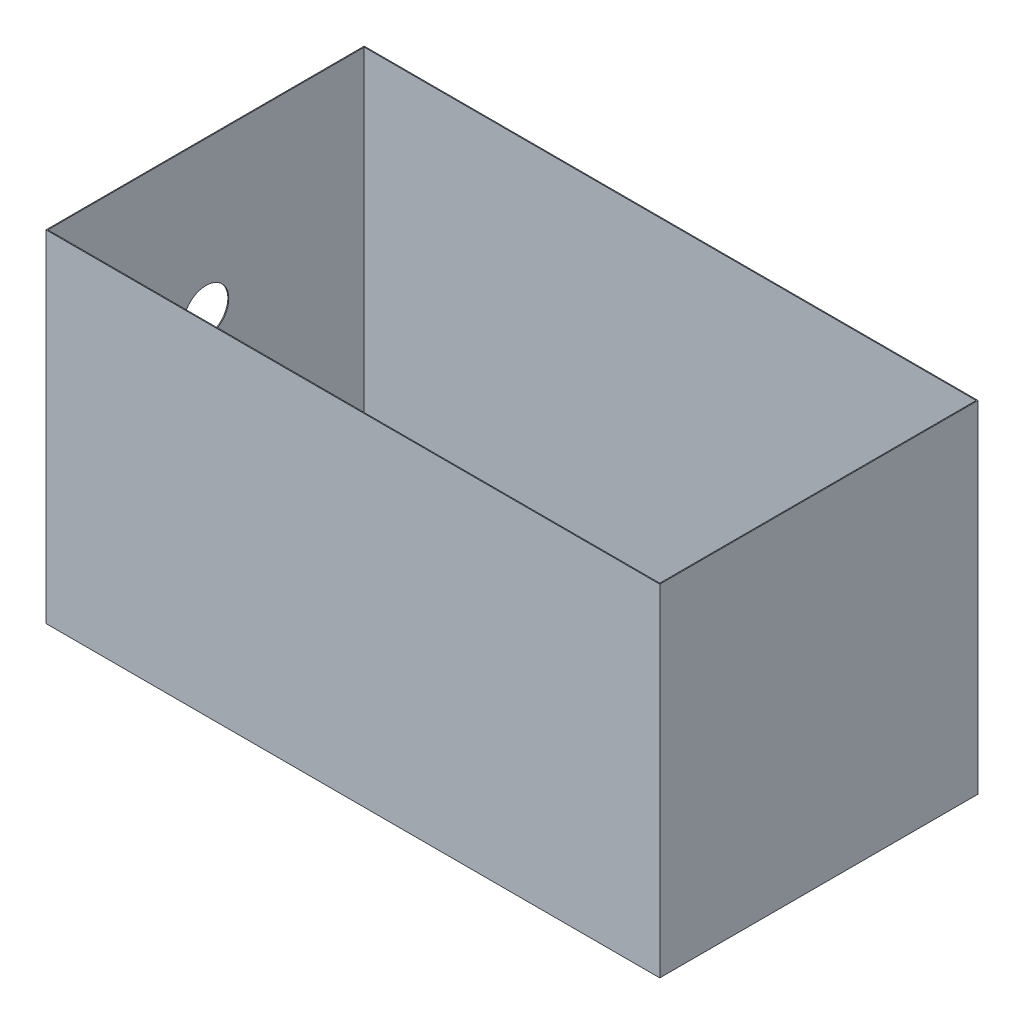
SolidWorks part; units mm, degrees
ref_plane "Спереди" through (0, 0, 0) normal (0, 0, 1) x (1, 0, 0)
ref_plane "Сверху" through (0, 0, 0) normal (0, 1, 0) x (1, 0, 0)
ref_plane "Справа" through (0, 0, 0) normal (1, 0, 0) x (0, 0, -1)
sketch "MASTER_FOOTPRINT" plane through (0, 0, 0) normal (0, 1, 0) x (1, 0, 0)
  line L1 (0, 0) -> (1350, 0)
  line L2 (0, 0) -> (0, 700)
  line L3 (0, 700) -> (1350, 700)
  line L4 (1350, 0) -> (1350, 700)
  dimension "D1" = 1350
  dimension "D2" = 700
extrude "BATH_BASE_PLATE" add sketch "MASTER_FOOTPRINT" along normal blind 750
shell "BATH_SHELL_2MM" thickness 2
sketch "Эскиз1" plane through (0, 0, 0) normal (1, 0, 0) x (0, 0, -1)
  circle A0 centre (350, 420) radius 50
extrude "INLET_D100_CUT" cut sketch "Эскиз1" along normal blind 10
equation "\"AI_Q_Peak\"= 0.006"
equation "\"AI_B_Bath\"= 700"
equation "\"AI_L_Settle\"= 900"
equation "\"AI_L_Inlet\"= 250"
equation "\"AI_L_Outlet\"= 200"
equation "\"AI_L_Bath\"= 1350"
equation "\"AI_H_Water\"= 550"
equation "\"AI_H_Freeboard\"= 200"
equation "\"AI_H_Bath\"= 750"
equation "\"AI_Shell_Thickness\"= 2"
equation "\"AI_Inlet_DN\"= 100"
equation "\"AI_Weir_Width\"= 600"
equation "\"AI_Inlet_Baffle_Offset\"= 125"
equation "\"AI_Distributor_Open_Area\"= 0.28"
equation "\"AI_Distributor_Hole_Dia\"= 22"
equation "\"AI_Distributor_Blind_Zone\"= 110"
equation "\"AI_Outlet_Baffle_Depth\"= 250"
equation "\"AI_Screw_Diameter\"= 100"
equation "\"AI_Screw_Pitch\"= 100"
equation "\"AI_Screw_Angle\"= 30"
equation "\"AI_Screw_Rpm\"= 15"
equation "\"AI_Screw_Clearance\"= 5"
equation "\"AI_Liner_Thickness\"= 5"
equation "\"AI_Discharge_Height\"= 650"
equation "\"AI_Frame_Height\"= 500"
equation "\"D1@MASTER_FOOTPRINT\" = \"AI_L_Bath\""
equation "\"D2@MASTER_FOOTPRINT\" = \"AI_B_Bath\""
equation "\"D1@BATH_BASE_PLATE\" = \"AI_H_Bath\""
